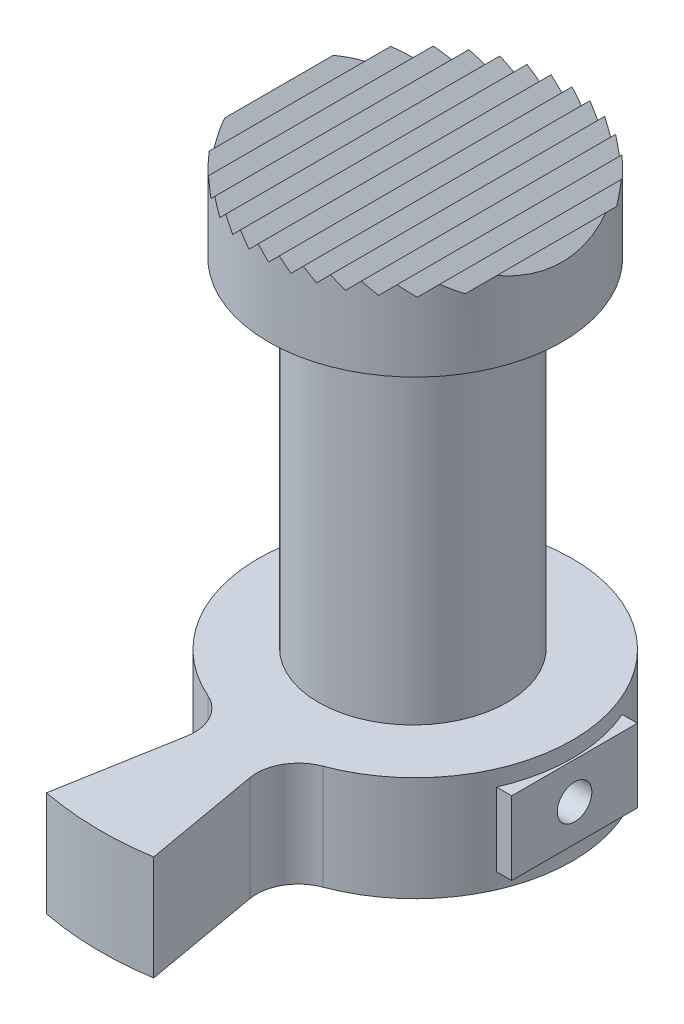
SolidWorks part; units mm, degrees
other "Camera1"
ref_plane "Front Plane" through (0, 0, 0) normal (0, 0, 1) x (1, 0, 0)
ref_plane "Top Plane" through (0, 0, 0) normal (0, 1, 0) x (1, 0, 0)
ref_plane "Right Plane" through (0, 0, 0) normal (1, 0, 0) x (0, 0, -1)
sketch "Sketch1" plane through (0, 0, 0) normal (0, 1, 0) x (1, 0, 0)
  circle A0 centre (0, 0) radius 7.5
  dimension "D1" = 15
extrude "Boss-Extrude1" add sketch "Sketch1" along normal blind 5 contours A0
sketch "Sketch2" plane through (0, 5, 0) normal (0, 1, 0) x (1, 0, 0)
  circle A0 centre (0, 0) radius 7
  dimension "D1" = 14
extrude "Boss-Extrude2" add sketch "Sketch2" along normal blind 20
sketch "Sketch5" plane through (0, 0, 0) normal (0, 0, 1) x (1, 0, 0)
  line L0 (7, 25) -> (-7, 25) construction
  line L1 (-7.502, 25) -> (-7, 24.498)
  line L2 (-7, 24.498) -> (-6.502, 25)
  line L3 (-6.502, 25) -> (-6, 24.498)
  line L4 (-6, 24.498) -> (-5.502, 25)
  line L5 (-5.502, 25) -> (-5, 24.498)
  line L6 (-5, 24.498) -> (-4.502, 25)
  line L7 (-4.502, 25) -> (-4, 24.498)
  line L8 (-4, 24.498) -> (-3.502, 25)
  line L9 (-3.502, 25) -> (-3, 24.498)
  line L10 (-3, 24.498) -> (-2.502, 25)
  line L11 (-2.502, 25) -> (-2, 24.498)
  line L12 (-2, 24.498) -> (-1.502, 25)
  line L13 (-1.502, 25) -> (-1, 24.498)
  line L14 (-1, 24.498) -> (-0.502, 25)
  line L15 (-0.502, 25) -> (0, 24.498)
  line L16 (0, 24.498) -> (0.498, 25)
  line L17 (0.498, 25) -> (1, 24.498)
  line L18 (1, 24.498) -> (1.498, 25)
  line L19 (1.498, 25) -> (2, 24.498)
  line L20 (2, 24.498) -> (2.498, 25)
  line L21 (2.498, 25) -> (3, 24.498)
  line L22 (3, 24.498) -> (3.498, 25)
  line L23 (3.498, 25) -> (4, 24.498)
  line L24 (4, 24.498) -> (4.498, 25)
  line L25 (4.498, 25) -> (5, 24.498)
  line L26 (5, 24.498) -> (5.498, 25)
  line L27 (5.498, 25) -> (6, 24.498)
  line L28 (6, 24.498) -> (6.498, 25)
  line L29 (6.498, 25) -> (7, 24.498)
  line L30 (7, 24.498) -> (7, 25.5056)
  line L31 (7, 25.5056) -> (-7.502, 25.5056)
  line L32 (-7.502, 25.5056) -> (-7.502, 25)
  point P0 (-7.502, 25)
  point P5 (-6.502, 25)
  point P6 (-5.502, 25)
  point P7 (-4.502, 25)
  point P8 (-3.502, 25)
  point P9 (-2.502, 25)
  point P10 (-1.502, 25)
  point P11 (-0.502, 25)
  point P12 (0.498, 25)
  point P13 (1.498, 25)
  point P14 (2.498, 25)
  point P15 (3.498, 25)
  point P16 (4.498, 25)
  point P17 (5.498, 25)
  point P18 (6.498, 25)
  point P19 (-6, 24.498)
  point P20 (-5, 24.498)
  point P21 (-4, 24.498)
  point P22 (-3, 24.498)
  point P23 (-2, 24.498)
  point P24 (-1, 24.498)
  point P25 (0, 24.498)
  point P26 (1, 24.498)
  point P27 (2, 24.498)
  point P28 (3, 24.498)
  point P29 (4, 24.498)
  point P30 (5, 24.498)
  point P31 (6, 24.498)
  point P32 (7, 24.498)
  point P33 (-7, 24.498)
  dimension "D1" = 15
  dimension "D2" = 2
extrude "Cut-Extrude2" cut sketch "Sketch5" against normal through all both and the other way through all
sketch "Sketch6" plane through (0, 0, 0) normal (0, -1, 0) x (1, 0, 0)
  circle A0 centre (0, 0) radius 1.3
  dimension "D1" = 2.6
extrude "Cut-Extrude3" cut sketch "Sketch6" against normal blind 0.7
sketch "Sketch9" plane through (0, 0.7, 0) normal (0, -1, 0) x (1, 0, 0)
  circle A3 centre (0, 0) radius 0.8
  dimension "D1" = 1.6
extrude "Cut-Extrude4" cut sketch "Sketch9" against normal blind 7
ref_plane "Plane1" through (7.5, 0, 0) normal (1, 0, 0) x (0, 0, -1)
sketch "Sketch10" plane through (7.5, 0, 0) normal (1, 0, 0) x (0, 0, -1)
  line L0 (7.5, 5) -> (-7.5, 5) construction
  line L1 (-3, 4.25) -> (3, 4.25)
  line L2 (-3, 4.25) -> (-3, 0.75)
  line L3 (-3, 0.75) -> (3, 0.75)
  line L4 (3, 4.25) -> (3, 0.75)
  line L5 (-3, 4.25) -> (3, 0.75) construction
  line L6 (-3, 0.75) -> (3, 4.25) construction
  point P0 (0, 2.5)
  dimension "D1" = 2.5
  dimension "D2" = 3.5
  dimension "D3" = 6
extrude "Boss-Extrude3" add sketch "Sketch10" along normal blind 0.1 and the other way blind 1
sketch "Sketch11" plane through (7.6, 0, 0) normal (1, 0, 0) x (0, 0, -1)
  circle A0 centre (0, 2.5) radius 0.825
  point P0 (0, 2.5)
  dimension "D1" = 1.65
sketch "Sketch17" plane through (0, 5, 0) normal (0, 1, 0) x (1, 0, 0)
  circle A0 centre (0, 0) radius 7.5
  circle A1 centre (-0.114, 0) radius 4.5
  dimension "D1" = 9
extrude "Cut-Extrude7" cut sketch "Sketch17" along normal blind 16.2
sketch "Sketch20" plane through (0, 0, 0) normal (0, -1, 0) x (1, 0, 0)
  line L2 (0.7067, 5.5703) -> (2.3371, 14.8168)
  line L3 (-2.8715, 14.7226) -> (-1.2411, 5.4761)
  arc A0 (-0.2713, 14.9975) -> (-2.8715, 14.7226) centre (0, 0) ccw
  arc A1 (-0.2713, 14.9975) -> (2.3371, 14.8168) centre (0, 0) cw
  arc A2 (-0.2713, 5.6084) -> (-1.2411, 5.4761) centre (0, 0) ccw
  arc A3 (-0.2713, 5.6084) -> (0.7067, 5.5703) centre (0, 0) cw
extrude "Boss-Extrude6" add sketch "Sketch20" against normal blind 5
fillet "Fillet2" radius 2 2 edges at (1.0343, 2.5, 7.4283) (-1.5687, 2.5, 7.3341)
extrude "Cut-Extrude8" cut sketch "Sketch11" against normal blind 7.5
